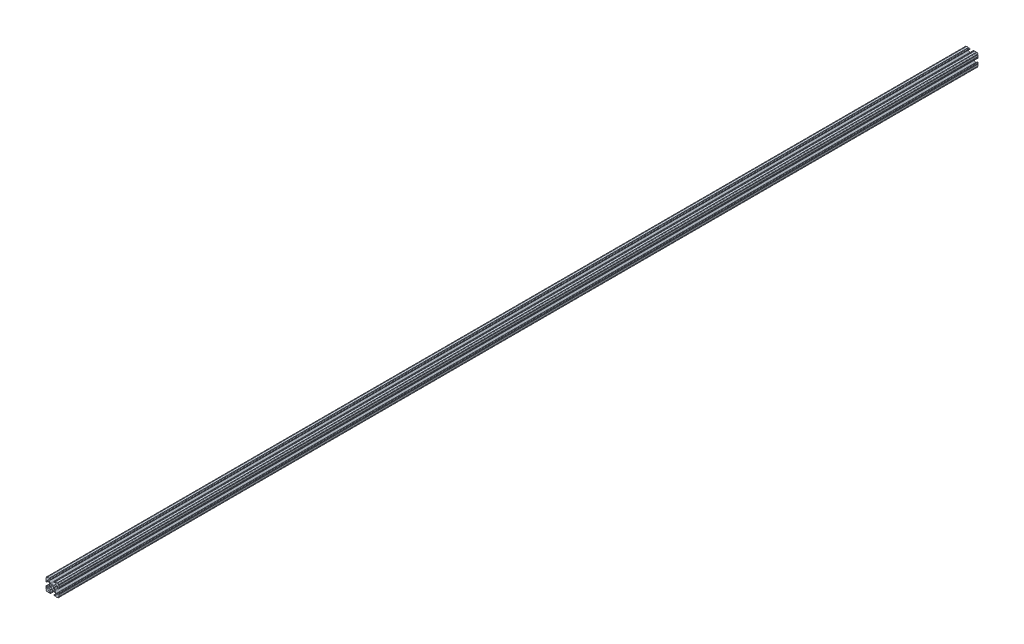
SolidWorks part; units mm, degrees
ref_plane "Front Plane" through (0, 0, 0) normal (0, 0, 1) x (1, 0, 0)
ref_plane "Top Plane" through (0, 0, 0) normal (0, 1, 0) x (1, 0, 0)
ref_plane "Right Plane" through (0, 0, 0) normal (1, 0, 0) x (0, 0, -1)
sketch "Sketch2" plane through (0, 0, 0) normal (0, 0, 1) x (1, 0, 0)
  line L0 (0, 12.7) -> (0, -12.7) construction
  line L1 (-12.7, 0) -> (12.7, 0) construction
  line L2 (3.2512, -12.7) -> (12.7, -12.7)
  line L3 (12.7, -12.7) -> (12.7, -3.2512)
  line L4 (3.2512, -12.7) -> (3.2512, -10.4902)
  line L5 (3.2512, -10.4902) -> (8.9276, -10.4902)
  line L6 (8.9276, -10.4902) -> (3.0856, -4.6482)
  line L7 (0, 0) -> (12.7, -12.7) construction
  line L8 (12.7, -3.2512) -> (10.4902, -3.2512)
  line L9 (10.4902, -3.2512) -> (10.4902, -8.9276)
  line L10 (10.4902, -8.9276) -> (4.6482, -3.0856)
  circle A0 centre (0, 0) radius 2.6035
  arc A1 (6.3485, -10.4902) -> (7.1039, -8.6665) centre (6.3485, -9.4219) ccw construction
  point P8 (0, -4.6482)
  dimension "Center Hole Diameter" = 5.207
  dimension "Rail Height" = 25.4
  dimension "Rail Width" = 25.4
  dimension "T-Slot Width" = 6.5024
  dimension "Slot Inner Width" = 14.8336
  dimension "Thickness" = 2.2098
  dimension "Slot Depth" = 5.842
  dimension "D1" = 2.2098
sketch "Sketch3" plane through (0, 0, 0) normal (1, 0, 0) x (0, 0, -1)
  line L0 (-1524, -12.7) -> (1524, -12.7) construction
  line L1 (-1498.6, 0) -> (1498.6, 0) construction
  dimension "Length" = 3048
  dimension "D1" = 25.4
sketch "Sketch4" plane through (0, 0, 0) normal (0, 0, 1) x (1, 0, 0)
  line L0 (4.1904, -12.7) -> (10.1173, -12.7)
  line L1 (3.2512, -12.7) -> (12.7, -12.7) construction
  line L2 (3.2512, -12.7) -> (3.2512, -10.4902) construction
  line L3 (3.2512, -10.4902) -> (8.9276, -10.4902) construction
  line L4 (3.2512, -11.4294) -> (3.2512, -11.7608)
  line L5 (4.1904, -10.4902) -> (6.3485, -10.4902)
  line L6 (0, -4.6482) -> (2.164, -4.6482)
  line L7 (8.9276, -10.4902) -> (3.0856, -4.6482) construction
  line L8 (3.7373, -5.2999) -> (7.1039, -8.6665)
  line L9 (12.7, -12.7) -> (12.7, -3.2512) construction
  line L10 (10.4902, -8.9276) -> (4.6482, -3.0856) construction
  line L11 (10.4902, -3.2512) -> (10.4902, -8.9276) construction
  line L12 (10.4902, -6.3485) -> (10.4902, -4.1904)
  line L13 (12.7, -3.2512) -> (10.4902, -3.2512) construction
  line L14 (11.4294, -3.2512) -> (11.7608, -3.2512)
  line L15 (12.7, -4.1904) -> (12.7, -10.1173)
  line L16 (8.6665, -7.1039) -> (5.2999, -3.7373)
  line L17 (4.6482, 0) -> (4.6482, -2.164)
  line L18 (-12.7, 0) -> (12.7, 0) construction
  line L19 (0, -4.6482) -> (0, -2.6035)
  line L20 (0, 12.7) -> (0, -12.7) construction
  line L21 (4.6482, 0) -> (2.6035, 0)
  arc A0 (3.2512, -11.7608) -> (4.1904, -12.7) centre (4.1904, -11.7608) ccw
  arc A2 (3.2512, -11.4294) -> (4.1904, -10.4902) centre (4.1904, -11.4294) cw
  arc A3 (6.3485, -10.4902) -> (7.1039, -8.6665) centre (6.3485, -9.4219) ccw
  arc A4 (2.164, -4.6482) -> (3.7373, -5.2999) centre (2.164, -6.8732) cw
  arc A5 (10.1173, -12.7) -> (12.7, -10.1173) centre (10.1173, -10.1173) ccw
  arc A6 (8.6665, -7.1039) -> (10.4902, -6.3485) centre (9.4219, -6.3485) ccw
  arc A7 (10.4902, -4.1904) -> (11.4294, -3.2512) centre (11.4294, -4.1904) cw
  arc A8 (11.7608, -3.2512) -> (12.7, -4.1904) centre (11.7608, -4.1904) cw
  arc A9 (5.2999, -3.7373) -> (4.6482, -2.164) centre (6.8732, -2.164) cw
  circle A10 centre (0, 0) radius 2.6035 construction
  arc A11 (0, -2.6035) -> (2.6035, 0) centre (0, 0) ccw
  dimension "D1" = 2.5827
  dimension "D2" = 2.225
  dimension "D3" = 0.9392
extrude "Boss-Extrude1" add sketch "Sketch4" along normal mid plane 3048
sketch "Sketch5" plane through (0, 0, 0) normal (0, 0, 1) x (1, 0, 0)
  line L0 (3.2512, -12.7) -> (12.7, -12.7) construction
  line L1 (4.1904, -10.4902) -> (6.3485, -10.4902) construction
  line L3 (0, 0) -> (12.7, -12.7) construction
  line L4 (6.3485, -10.4902) -> (6.3485, -12.7) construction
  line L5 (8.9276, -10.4902) -> (3.0856, -4.6482) construction
  circle A0 centre (10.3562, -12.7) radius 0.5524
  circle A1 centre (5.796, -12.7) radius 0.5524
  circle A2 centre (12.7, -10.3562) radius 0.5524
  circle A3 centre (12.7, -5.796) radius 0.5524
  point P10 (5.2694, -10.4902)
  point P12 (9.4219, -6.3485)
  dimension "D1" = 1.1049
extrude "Cut-Extrude1" cut sketch "Sketch5" against normal through all both and the other way through all
mirror "Mirror1" about plane through (0, 0, 0) normal (1, 0, 0) of bodies 137 134
mirror "Mirror2" about plane through (0, 0, 0) normal (0, 1, 0) of bodies 135
sketch "Sketch8" plane through (0, 0, 0) normal (0, 1, 0) x (1, 0, 0)
  line L0 (-12.58, 1524) -> (-12.58, -1524) construction
  line L1 (-25.28, 1536.7) -> (25.28, 1536.7)
  line L2 (-25.28, 1536.7) -> (-25.28, 304.8)
  line L3 (-25.28, 304.8) -> (25.28, 304.8)
  line L4 (25.28, 1536.7) -> (25.28, 304.8)
  line L5 (12.58, 1524) -> (12.58, -1524) construction
  line L6 (-6.3485, 1524) -> (-9.8037, 1524) construction
  dimension "D1" = 12.7
  dimension "D2" = 12.7
  dimension "D3" = 12.7
  dimension "D4" = 1219.2
extrude "Cut-Extrude2" cut sketch "Sketch8" against normal through all both and the other way through all
equation "\"D1@Boss-Extrude1\"=\"Length@Sketch3\""
equation "\"D1@Sketch2\"=\"Thickness@Sketch2\""
equation "\"D2@Sketch4\"=\"Slot Inner Width@Sketch2\"*0.15"
equation "\"D1@Sketch4\"=\"D3@Sketch4\"*2.75"
equation "\"D3@Sketch4\"=\"Thickness@Sketch2\"*0.425"
equation "\"D1@Sketch5\"=\"Thickness@Sketch2\"*0.5"
